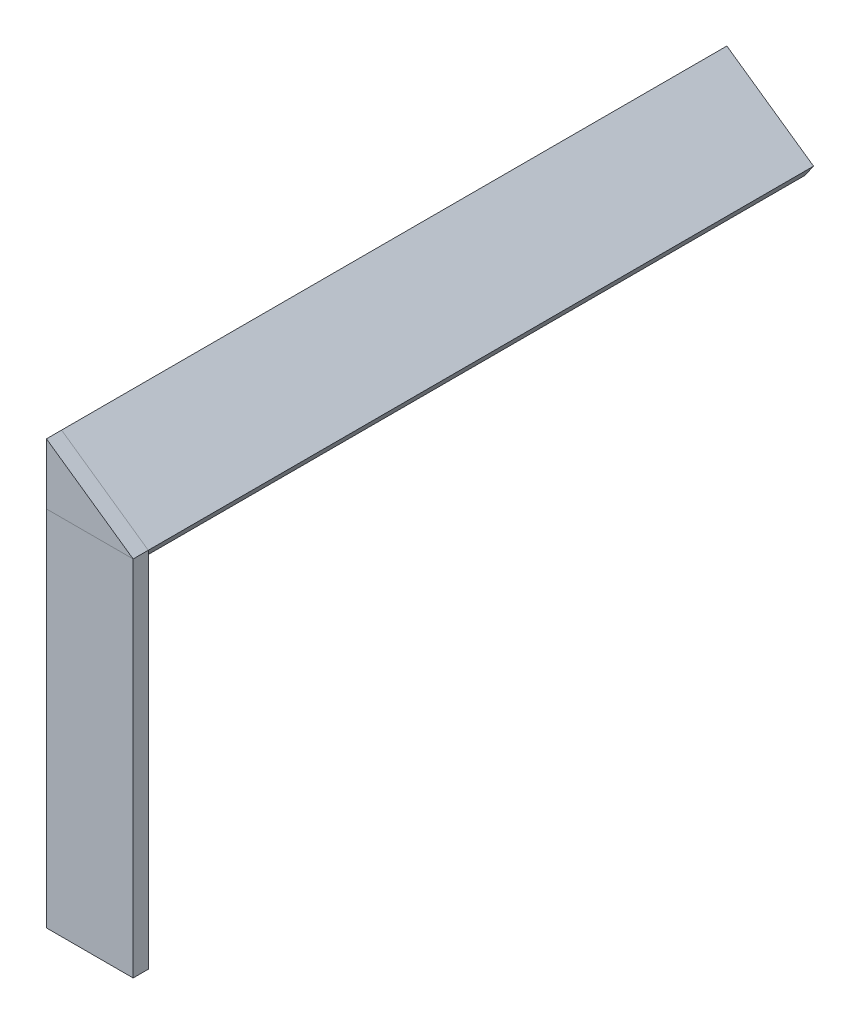
SolidWorks part; units mm, degrees
ref_plane "Front Plane" through (0, 0, 0) normal (0, 0, 1) x (1, 0, 0)
ref_plane "Top Plane" through (0, 0, 0) normal (0, 1, 0) x (1, 0, 0)
ref_plane "Right Plane" through (0, 0, 0) normal (1, 0, 0) x (0, 0, -1)
sketch "Sketch1" plane through (0, 0, 0) normal (0, 0, 1) x (1, 0, 0)
  line L0 (-18.2057, 25.4955) -> (18.2057, 0)
  line L1 (18.2057, 0) -> (-18.2057, 0)
  line L2 (-18.2057, 0) -> (-18.2057, 25.4955)
  point P2 (0, 0)
  dimension "D1" = 44.45
  dimension "D2" = 55
extrude "Boss-Extrude1" add sketch "Sketch1" along normal blind 6.35
sketch "Sketch2" plane through (0, 0, 0) normal (0, 0, 1) x (1, 0, 0)
  line L1 (-18.2057, 0) -> (18.2057, 0) construction
  line L2 (-18.2057, 0) -> (18.2057, 0)
  line L3 (-18.2057, 0) -> (-18.2057, -152.4)
  line L4 (-18.2057, -152.4) -> (18.2057, -152.4)
  line L5 (18.2057, 0) -> (18.2057, -152.4)
  point P6 (0, 0)
  point P7 (0, 0)
  dimension "D1" = 152.4
extrude "Boss-Extrude2" add sketch "Sketch2" along normal blind 6.35 separate body
sketch "Sketch3" plane through (0, 0, 0) normal (0, 0, 1) x (1, 0, 0)
  line L0 (-18.2057, 25.4955) -> (18.2057, 0)
  line L1 (-18.2057, 25.4955) -> (-21.8479, 20.2939)
  line L2 (18.2057, 0) -> (14.5634, -5.2016)
  line L3 (-21.8479, 20.2939) -> (14.5634, -5.2016)
  dimension "D1" = 6.35
extrude "Boss-Extrude3" add sketch "Sketch3" against normal blind 279.4 separate body
